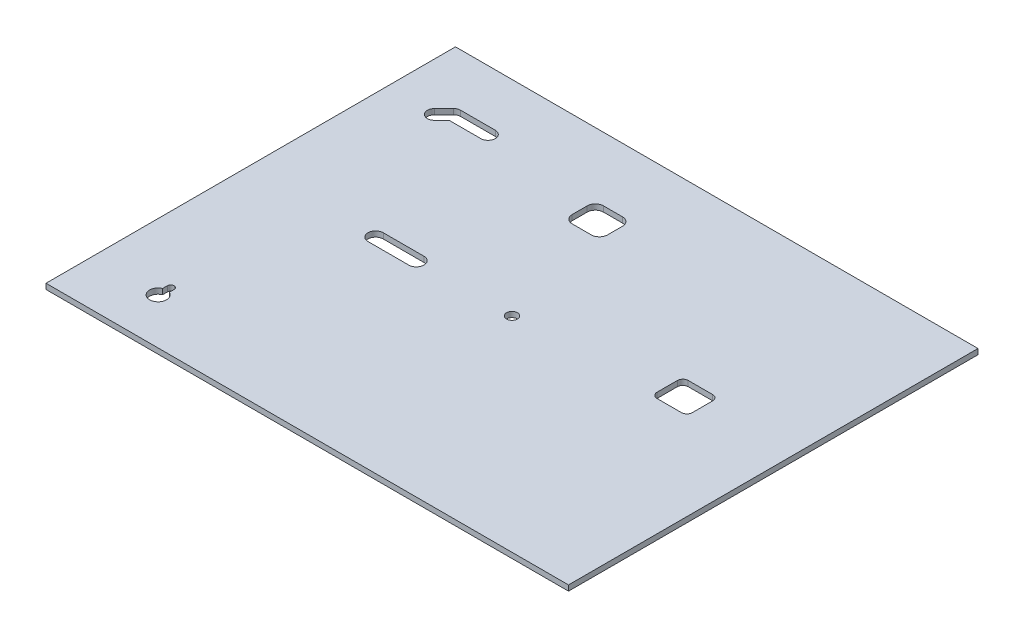
SolidWorks part; units mm, degrees
ref_plane "Front Plane" through (0, 0, 0) normal (0, 0, 1) x (1, 0, 0)
ref_plane "Top Plane" through (0, 0, 0) normal (0, 1, 0) x (1, 0, 0)
ref_plane "Right Plane" through (0, 0, 0) normal (1, 0, 0) x (0, 0, -1)
sketch "Sketch1" plane through (0, 0, 0) normal (0, 1, 0) x (1, 0, 0)
  line L1 (-961.3511, -753.4273) -> (961.3511, -753.4273)
  line L2 (-961.3511, -753.4273) -> (-961.3511, 753.4273)
  line L3 (-961.3511, 753.4273) -> (961.3511, 753.4273)
  line L4 (961.3511, -753.4273) -> (961.3511, 753.4273)
  line L5 (-961.3511, -753.4273) -> (961.3511, 753.4273) construction
  line L6 (-961.3511, 753.4273) -> (961.3511, -753.4273) construction
  point P0 (0, 0)
extrude "Boss-Extrude1" add sketch "Sketch1" along normal blind 20
sketch "Sketch2" plane through (0, 20, 0) normal (0, 1, 0) x (1, 0, 0)
  circle A0 centre (0, 0) radius 20.1212
  dimension "D1" = 40.2424
extrude "Cut-Extrude1" cut sketch "Sketch2" against normal blind 20
sketch "Sketch3" plane through (0, 20, 0) normal (0, 1, 0) x (1, 0, 0)
  line L0 (-501.8539, 0) -> (-351.8539, 0) construction
  line L1 (-501.8539, 28.0827) -> (-351.8539, 28.0827)
  line L2 (-501.8539, -28.0827) -> (-351.8539, -28.0827)
  arc A0 (-501.8539, 28.0827) -> (-501.8539, -28.0827) centre (-501.8539, 0) ccw
  arc A1 (-351.8539, -28.0827) -> (-351.8539, 28.0827) centre (-351.8539, 0) ccw
  point P3 (-426.8539, 0)
  dimension "D1" = 28.0827
  dimension "D2" = 150
extrude "Cut-Extrude2" cut sketch "Sketch3" against normal through all
sketch "Sketch4" plane through (0, 20, 0) normal (0, 1, 0) x (1, 0, 0)
  line L1 (530.1115, 3.4306) -> (620.1115, 3.4306)
  line L2 (510.1115, 23.4306) -> (510.1115, 98.4306)
  line L3 (530.1115, 118.4306) -> (620.1115, 118.4306)
  line L4 (640.1115, 23.4306) -> (640.1115, 98.4306)
  arc A0 (510.1115, 98.4306) -> (530.1115, 118.4306) centre (530.1115, 98.4306) cw
  arc A1 (640.1115, 98.4306) -> (620.1115, 118.4306) centre (620.1115, 98.4306) ccw
  arc A2 (640.1115, 23.4306) -> (620.1115, 3.4306) centre (620.1115, 23.4306) cw
  arc A3 (530.1115, 3.4306) -> (510.1115, 23.4306) centre (530.1115, 23.4306) cw
  dimension "D3" = 20
  dimension "D1" = 130
  dimension "D2" = 115
extrude "Cut-Extrude3" cut sketch "Sketch4" against normal through all contours L3 A1 L4 A2 L1 A3 L2 A0
sketch "Sketch5" plane through (0, 20, 0) normal (0, 1, 0) x (1, 0, 0)
  line L1 (-182.264, 403.8948) -> (-112.264, 403.8948)
  line L2 (-212.264, 433.8948) -> (-212.264, 488.8948)
  line L3 (-182.264, 518.8948) -> (-112.264, 518.8948)
  line L4 (-82.264, 433.8948) -> (-82.264, 488.8948)
  arc A0 (-212.264, 488.8948) -> (-182.264, 518.8948) centre (-182.264, 488.8948) cw
  arc A1 (-82.264, 488.8948) -> (-112.264, 518.8948) centre (-112.264, 488.8948) ccw
  arc A2 (-82.264, 433.8948) -> (-112.264, 403.8948) centre (-112.264, 433.8948) cw
  arc A3 (-182.264, 403.8948) -> (-212.264, 433.8948) centre (-182.264, 433.8948) cw
  point P0 (-102.264, 403.8948)
  dimension "D3" = 30
  dimension "D1" = 130
  dimension "D2" = 115
extrude "Cut-Extrude4" cut sketch "Sketch5" against normal through all and the other way through all contours L3 A1 L4 A2 L1 A3 L2 A0
sketch "Sketch6" plane through (0, 20, 0) normal (0, 1, 0) x (1, 0, 0)
  line L0 (-784.1855, 499.6178) -> (-749.5884, 534.2149) construction
  line L1 (-803.0449, 518.4771) -> (-768.4477, 553.0742)
  line L2 (-765.3262, 480.7585) -> (-738.5409, 507.5438)
  line L3 (-749.5884, 534.2149) -> (-622.3189, 534.2149) construction
  line L4 (-749.5884, 560.886) -> (-622.3189, 560.886)
  line L5 (-738.5409, 507.5438) -> (-622.3189, 507.5438)
  arc A0 (-803.0449, 518.4771) -> (-765.3262, 480.7585) centre (-784.1855, 499.6178) ccw
  arc A1 (-749.5884, 560.886) -> (-768.4477, 553.0742) centre (-749.5884, 534.2149) ccw
  arc A3 (-622.3189, 507.5438) -> (-622.3189, 560.886) centre (-622.3189, 534.2149) ccw
  point P2 (0, 0)
  point P6 (0, 0)
  point P8 (-622.3189, 534.2149)
  point P12 (0, 0)
  dimension "D2" = 26.6711
  dimension "D3" = 26.6711
  dimension "D1" = 45
  dimension "D4" = 127.2695
  dimension "D5" = 48.9277
extrude "Cut-Extrude5" cut sketch "Sketch6" against normal through all
sketch "Sketch8" plane through (0, 20, 0) normal (0, 1, 0) x (1, 0, 0)
  line L1 (-730.1959, -555.4671) -> (-730.1959, -537.8889)
  line L2 (-705.7622, -555.4671) -> (-705.7622, -537.8889)
  arc A0 (-730.1959, -555.4671) -> (-705.7622, -555.4671) centre (-717.979, -584.2896) ccw
  arc A2 (-705.7622, -537.8889) -> (-730.1959, -537.8889) centre (-717.979, -537.8889) ccw
  point P3 (0, 0)
  point P4 (0, 0)
  point P6 (0, 0)
  point P8 (-717.979, -537.8889)
  point P9 (0, 0)
  point P11 (0, 0)
  dimension "D1" = 12.2168
  dimension "D2" = 31.3048
  dimension "D3" = 46.4007
extrude "Cut-Extrude6" cut sketch "Sketch8" against normal through all
